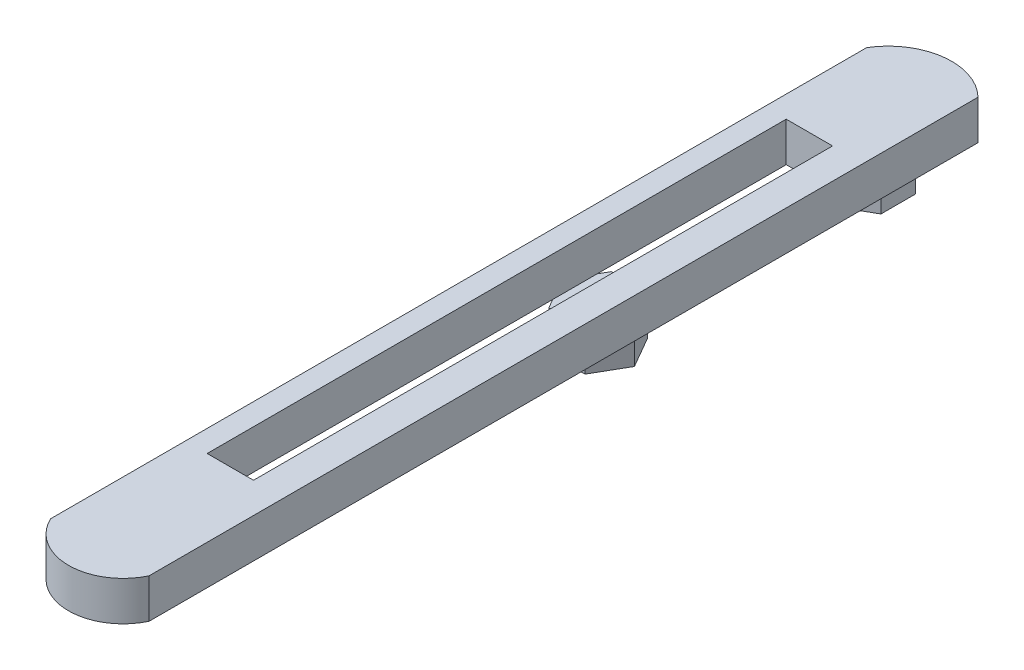
SolidWorks part; units mm, degrees
ref_plane "Front Plane" through (0, 0, 0) normal (0, 0, 1) x (1, 0, 0)
ref_plane "Top Plane" through (0, 0, 0) normal (0, 1, 0) x (1, 0, 0)
ref_plane "Right Plane" through (0, 0, 0) normal (1, 0, 0) x (0, 0, -1)
sketch "Sketch1" plane through (0, 0, 0) normal (0, 1, 0) x (1, 0, 0)
  line L2 (2.5, -24.8922) -> (2.5, 17.1683)
  line L4 (-2.5047, -24.8823) -> (-2.5047, 16.525)
  arc A0 (-2.5047, -24.8823) -> (2.5, -24.8922) centre (0, -23.7127) ccw
  arc A1 (2.5, 17.1683) -> (-2.5047, 16.525) centre (0.2527, 14.8621) ccw
  point P0 (0, 0)
  point P8 (-0.0329, 12.6444)
extrude "Boss-Extrude1" add sketch "Sketch1" along normal blind 2 contours L2 A1 L4 A0
sketch "Sketch3" plane through (0, 0, 0) normal (0, -1, 0) x (-1, 0, 0)
  line L1 (1.4011, -18.0441) -> (-0.951, -18.0441)
  line L2 (1.4011, -18.0441) -> (1.4011, 11.3375)
  line L3 (1.4011, 11.3375) -> (-0.951, 11.3375)
  line L4 (-0.951, -18.0441) -> (-0.951, 11.3375)
extrude "Cut-Extrude1" cut sketch "Sketch3" against normal blind 10
sketch "Sketch8" plane through (0, 0, 0) normal (0, -1, 0) x (-1, 0, 0)
  line L1 (0.3549, 16.2164) -> (-1.1696, 15.3363)
  line L2 (-1.1696, 15.3363) -> (-1.1696, 13.576)
  line L3 (-1.1696, 13.576) -> (0.3549, 12.6958)
  line L4 (0.3549, 12.6958) -> (1.8794, 13.576)
  line L5 (1.8794, 13.576) -> (1.8794, 15.3363)
  line L6 (1.8794, 15.3363) -> (0.3549, 16.2164)
  circle A0 centre (0.3549, 14.4561) radius 1.5245 construction
extrude "Boss-Extrude6" add sketch "Sketch8" along normal blind 2
sketch "Sketch9" plane through (0, 0, 0) normal (0, -1, 0) x (-1, 0, 0)
  line L1 (-1.6165, 0.6181) -> (-0.6994, -0.9704)
  line L2 (-0.6994, -0.9704) -> (1.1348, -0.9704)
  line L3 (1.1348, -0.9704) -> (2.0519, 0.6181)
  line L4 (2.0519, 0.6181) -> (1.1348, 2.2065)
  line L5 (1.1348, 2.2065) -> (-0.6994, 2.2065)
  line L6 (-0.6994, 2.2065) -> (-1.6165, 0.6181)
  circle A0 centre (0.2177, 0.6181) radius 1.5885 construction
  point P1 (0.2152, 3.2157)
  point P9 (0.1207, 0.7331)
  point P10 (0.2177, 0.6181)
extrude "Boss-Extrude9" add sketch "Sketch9" along normal blind 2
